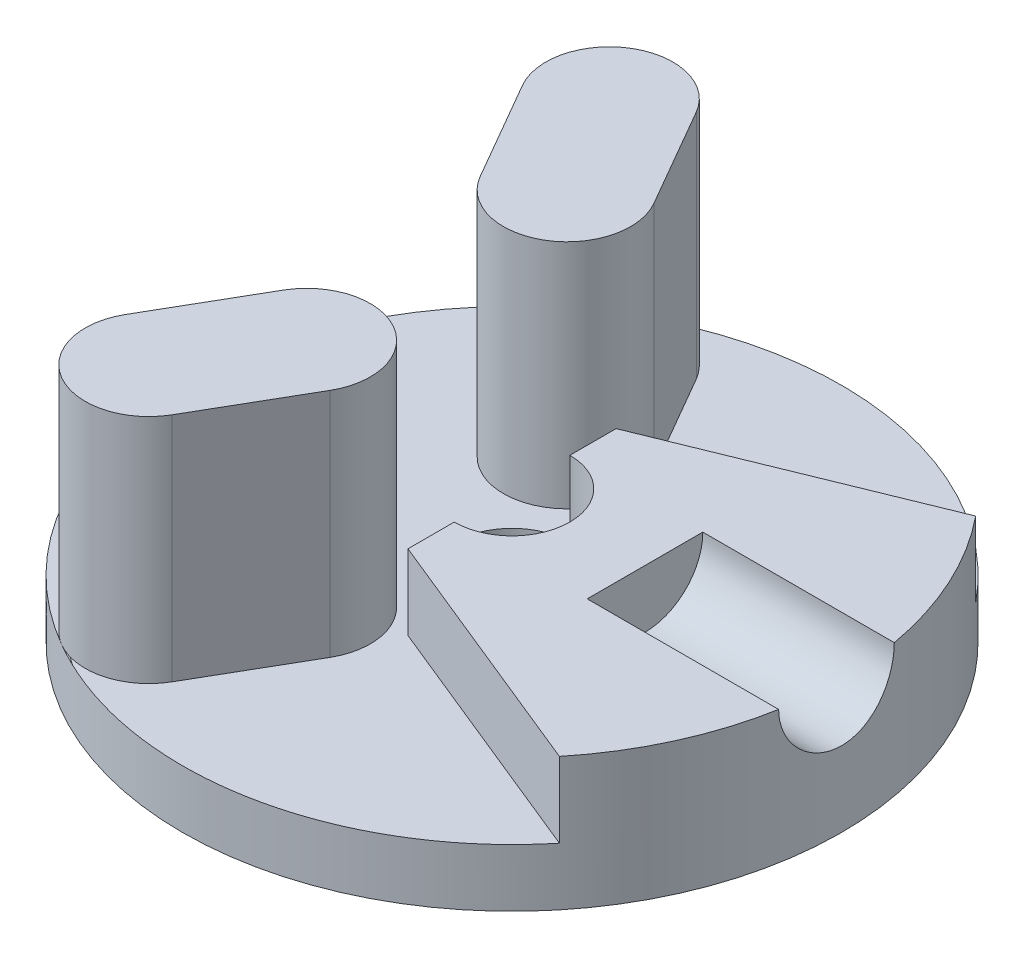
SolidWorks part; units mm, degrees
material "ABS"
ref_plane "前视基准面" through (0, 0, 0) normal (0, 0, 1) x (1, 0, 0)
ref_plane "上视基准面" through (0, 0, 0) normal (0, 1, 0) x (1, 0, 0)
ref_plane "右视基准面" through (0, 0, 0) normal (1, 0, 0) x (0, 0, -1)
sketch "Sketch1" plane through (0, 0, 0) normal (0, 1, 0) x (1, 0, 0)
  circle A0 centre (0, 0) radius 28.5
  circle A1 centre (0, 0) radius 5
  dimension "D1" = 57
  dimension "D2" = 10
extrude "Boss-Extrude1" add sketch "Sketch1" along normal blind 5
sketch "Sketch5" plane through (0, 5, 0) normal (0, 1, 0) x (1, 0, 0)
  line L0 (0, 9) -> (22.0964, 18)
  line L1 (0, -9) -> (22.0964, -18)
  line L2 (0, 0) -> (52.6815, 0) construction
  line L3 (0, -9) -> (0, -5)
  line L4 (0, -5) -> (0, 0) construction
  line L5 (0, 5) -> (0, 9)
  line L6 (0, 0) -> (0, 5) construction
  arc A1 (22.0964, -18) -> (22.0964, 18) centre (0, 0) ccw
  circle A2 centre (0, 0) radius 28.5 construction
  arc A4 (22.0964, 18) -> (22.0964, -18) centre (0, 0) ccw construction
  arc A5 (0, -5) -> (0, 5) centre (0, 0) ccw
  arc A6 (0, 5) -> (0, -5) centre (0, 0) ccw construction
  point P12 (0, 0)
  dimension "D1" = 0
  dimension "D3" = 18
extrude "Boss-Extrude3" add sketch "Sketch5" along normal blind 6.5
ref_plane "Plane1" through (28.5, 0, 0) normal (1, 0, 0) x (0, 0, -1)
sketch "Sketch6" plane through (28.5, 0, 0) normal (1, 0, 0) x (0, 0, -1)
  line L0 (18, 11.5) -> (-18, 11.5) construction
  circle A0 centre (0, 11.5) radius 5
  dimension "D1" = 10
extrude "Cut-Extrude1" cut sketch "Sketch6" against normal blind 17
sketch "Sketch8" plane through (0, 5, 0) normal (0, 1, 0) x (1, 0, 0)
  line L0 (0, 0) -> (-37.0055, 0) construction
  line L1 (-11.5, 19.9186) -> (-6.5, 11.2583) construction
  line L2 (-6.7369, 22.6686) -> (-1.7369, 14.0083)
  line L3 (-16.2631, 17.1686) -> (-11.2631, 8.5083)
  line L4 (-11.5, -19.9186) -> (-6.5, -11.2583) construction
  line L5 (-6.7369, -22.6686) -> (-1.7369, -14.0083)
  line L6 (-16.2631, -17.1686) -> (-11.2631, -8.5083)
  arc A2 (-6.7369, 22.6686) -> (-16.2631, 17.1686) centre (-11.5, 19.9186) ccw
  arc A3 (-11.2631, 8.5083) -> (-1.7369, 14.0083) centre (-6.5, 11.2583) ccw
  arc A4 (-6.7369, -22.6686) -> (-16.2631, -17.1686) centre (-11.5, -19.9186) cw
  arc A5 (-11.2631, -8.5083) -> (-1.7369, -14.0083) centre (-6.5, -11.2583) cw
  point P5 (-9, 15.5885)
  point P13 (-9, -15.5885)
  dimension "D1" = 60
  dimension "D3" = 5.5
  dimension "D2" = 10
  dimension "D4" = 13
extrude "Boss-Extrude4" add sketch "Sketch8" along normal blind 20
sketch "Sketch9" plane through (0, 0, 0) normal (0, 1, 0) x (1, 0, 0)
  circle A0 centre (0, 0) radius 13
  dimension "D1" = 26
extrude "Cut-Extrude2" cut sketch "Sketch9" along normal blind 4
